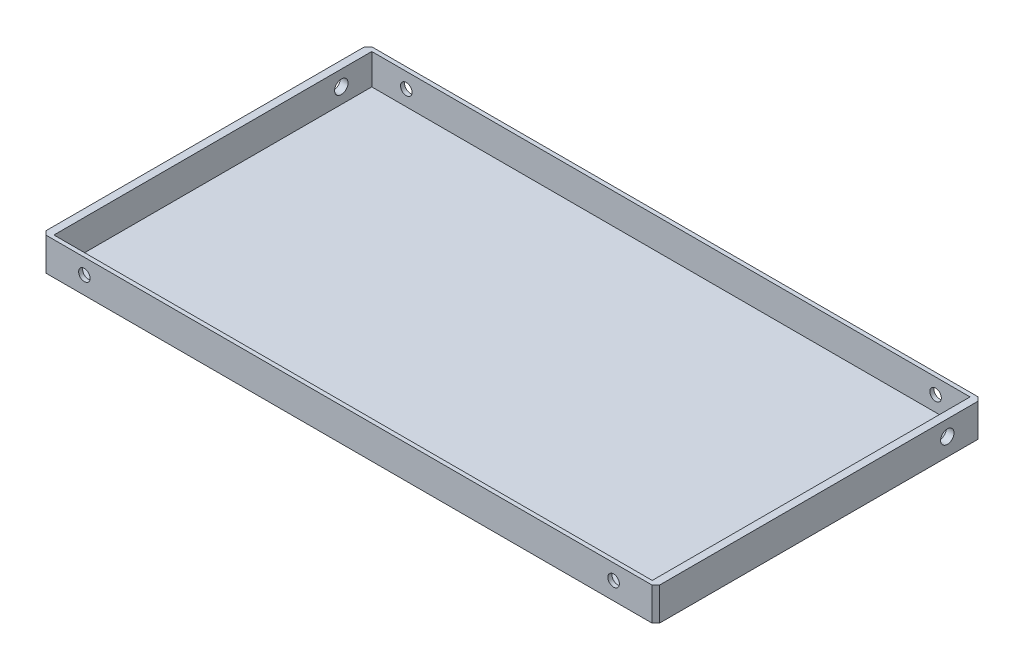
SolidWorks part; units mm, degrees
ref_plane "Front Plane" through (0, 0, 0) normal (0, 0, 1) x (1, 0, 0)
ref_plane "Top Plane" through (0, 0, 0) normal (0, 1, 0) x (1, 0, 0)
ref_plane "Right Plane" through (0, 0, 0) normal (1, 0, 0) x (0, 0, -1)
sketch "Sketch1" plane through (0, 0, 0) normal (0, 1, 0) x (1, 0, 0)
  line L1 (-80, 42.5) -> (80, 42.5)
  line L2 (-80, 42.5) -> (-80, -42.5)
  line L3 (-80, -42.5) -> (80, -42.5)
  line L4 (80, 42.5) -> (80, -42.5)
  line L5 (-80, 42.5) -> (80, -42.5) construction
  line L6 (-80, -42.5) -> (80, 42.5) construction
  point P0 (0, 0)
  dimension "D1" = 160
  dimension "D2" = 85
extrude "Boss-Extrude1" add sketch "Sketch1" along normal blind 0.6
sketch "Sketch2" plane through (0, 0.6, 0) normal (0, 1, 0) x (1, 0, 0)
  line L1 (-80, -42.5) -> (80, -42.5)
  line L2 (-80, -42.5) -> (-80, 42.5)
  line L3 (-80, 42.5) -> (80, 42.5)
  line L4 (80, -42.5) -> (80, 42.5)
  line L5 (-80, -42.5) -> (80, 42.5) construction
  line L6 (-80, 42.5) -> (80, -42.5) construction
  line L7 (-78, -41.4375) -> (78, -41.4375)
  line L8 (-78, -41.4375) -> (-78, 41.4375)
  line L9 (-78, 41.4375) -> (78, 41.4375)
  line L10 (78, -41.4375) -> (78, 41.4375)
  line L11 (-78, -41.4375) -> (78, 41.4375) construction
  line L12 (-78, 41.4375) -> (78, -41.4375) construction
  point P0 (0, 0)
  point P7 (0, 0)
  dimension "D1" = 2
extrude "Boss-Extrude2" add sketch "Sketch2" along normal blind 8
chamfer "Chamfer1" distance 1 angle 45 4 edges at (80, 4.3, -42.5) (-80, 4.3, -42.5) (80, 4.3, 42.5) (-80, 4.3, 42.5)
sketch "Sketch3" plane through (0, 0, 42.5) normal (0, 0, 1) x (1, 0, 0)
  line L0 (-79, 8.6) -> (-79, 0) construction
  line L1 (79, 0) -> (79, 8.6) construction
  line L2 (-79, 8.6) -> (79, 8.6) construction
  circle A0 centre (-69, 4.6) radius 1.5
  circle A1 centre (69, 4.6) radius 1.5
  dimension "D1" = 3
  dimension "D2" = 3
  dimension "D3" = 10
  dimension "D4" = 10
  dimension "D5" = 4
  dimension "D6" = 4
extrude "Cut-Extrude1" cut sketch "Sketch3" against normal blind 98
sketch "Sketch4" plane through (80, 0, 0) normal (1, 0, 0) x (0, 0, -1)
  line L0 (41.5, 0) -> (41.5, 8.6) construction
  line L1 (-41.5, 8.6) -> (41.5, 8.6) construction
  circle A0 centre (33.5, 4.6) radius 1.75
  dimension "D1" = 3.5
  dimension "D2" = 8
  dimension "D3" = 4
extrude "Cut-Extrude2" cut sketch "Sketch4" against normal blind 1000
